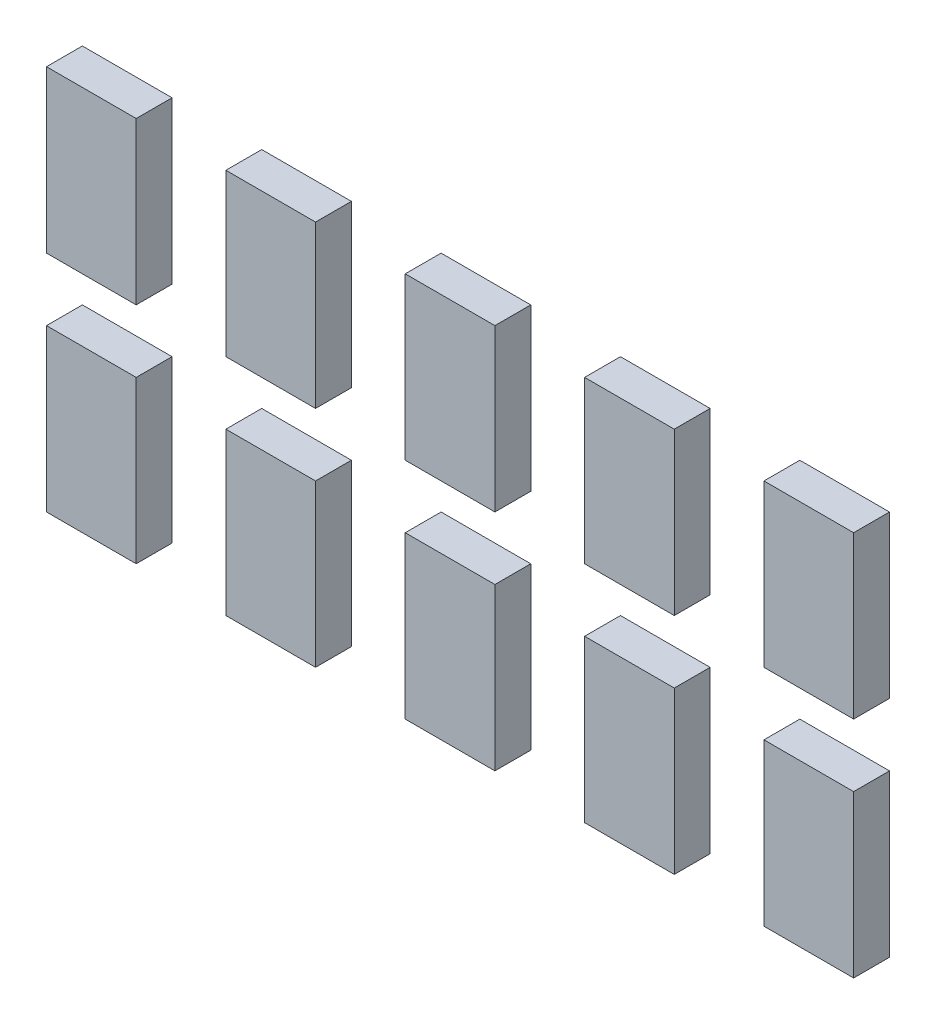
SolidWorks part; units mm, degrees
ref_plane "Спереди" through (0, 0, 0) normal (0, 0, 1) x (1, 0, 0)
ref_plane "Сверху" through (0, 0, 0) normal (0, 1, 0) x (1, 0, 0)
ref_plane "Справа" through (0, 0, 0) normal (1, 0, 0) x (0, 0, -1)
sketch "Эскиз1" plane through (0, 0, 0) normal (0, 0, 1) x (1, 0, 0)
  line L0 (3, -1.8) -> (5, -1.8)
  line L1 (-1, -1.8) -> (1, -1.8)
  line L2 (-1, -1.8) -> (-1, 1.8)
  line L3 (-1, 1.8) -> (1, 1.8)
  line L4 (1, -1.8) -> (1, 1.8)
  line L5 (-1, -1.8) -> (1, 1.8) construction
  line L6 (-1, 1.8) -> (1, -1.8) construction
  line L7 (5, -1.8) -> (5, 1.8)
  line L8 (3, 1.8) -> (5, 1.8)
  line L9 (3, -1.8) -> (3, 1.8)
  line L10 (7, -1.8) -> (9, -1.8)
  line L11 (9, -1.8) -> (9, 1.8)
  line L12 (7, 1.8) -> (9, 1.8)
  line L13 (7, -1.8) -> (7, 1.8)
  line L14 (11, -1.8) -> (13, -1.8)
  line L15 (13, -1.8) -> (13, 1.8)
  line L16 (11, 1.8) -> (13, 1.8)
  line L17 (11, -1.8) -> (11, 1.8)
  line L18 (15, -1.8) -> (17, -1.8)
  line L19 (17, -1.8) -> (17, 1.8)
  line L20 (15, 1.8) -> (17, 1.8)
  line L21 (15, -1.8) -> (15, 1.8)
  line L22 (3, 3.2) -> (5, 3.2)
  line L23 (5, 3.2) -> (5, 6.8)
  line L24 (3, 6.8) -> (5, 6.8)
  line L25 (3, 3.2) -> (3, 6.8)
  line L26 (7, 3.2) -> (9, 3.2)
  line L27 (9, 3.2) -> (9, 6.8)
  line L28 (7, 6.8) -> (9, 6.8)
  line L29 (7, 3.2) -> (7, 6.8)
  line L30 (11, 3.2) -> (13, 3.2)
  line L31 (13, 3.2) -> (13, 6.8)
  line L32 (11, 6.8) -> (13, 6.8)
  line L33 (11, 3.2) -> (11, 6.8)
  line L34 (15, 3.2) -> (17, 3.2)
  line L35 (17, 3.2) -> (17, 6.8)
  line L36 (15, 6.8) -> (17, 6.8)
  line L37 (15, 3.2) -> (15, 6.8)
  line L38 (-1, 3.2) -> (1, 3.2)
  line L39 (1, 3.2) -> (1, 6.8)
  line L40 (-1, 6.8) -> (1, 6.8)
  line L41 (-1, 3.2) -> (-1, 6.8)
  point P0 (0, 0)
  dimension "D1" = 2
  dimension "D2" = 3.6
  dimension "D3" = 5
  dimension "D4" = 2
extrude "Бобышка-Вытянуть1" add sketch "Эскиз1" along normal blind 0.8
